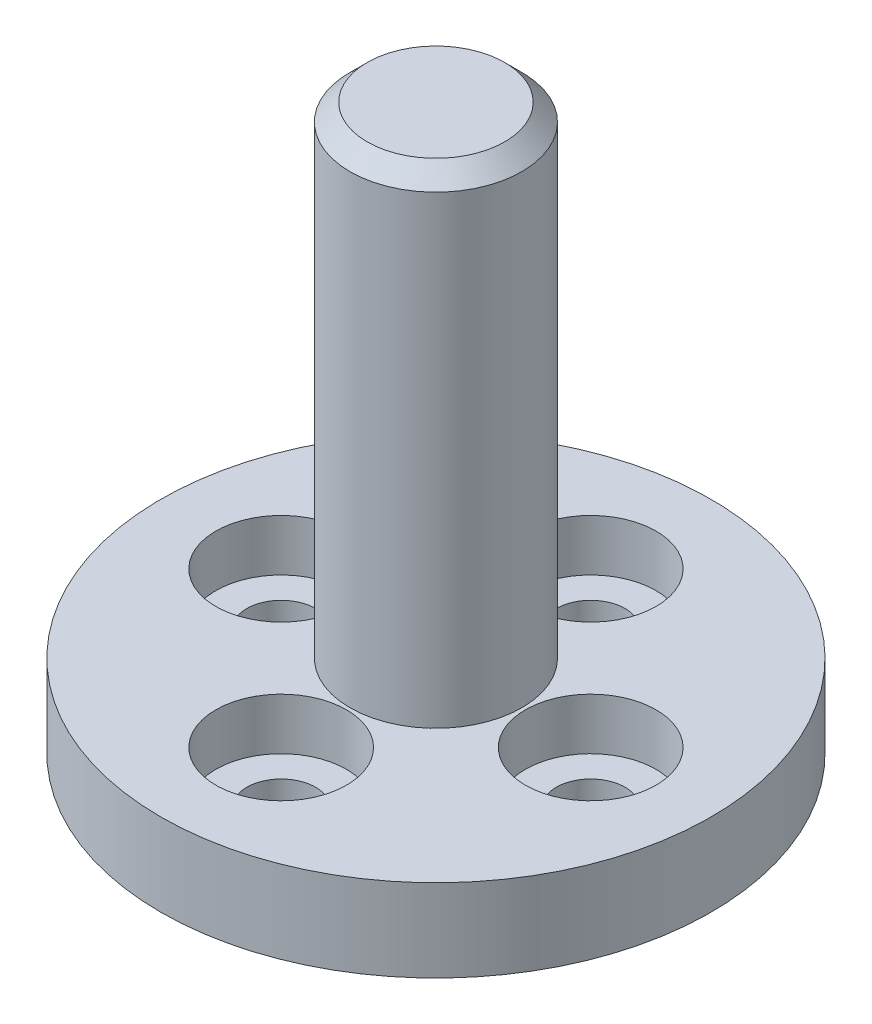
SolidWorks part; units mm, degrees
ref_plane "Plan de face" through (0, 0, 0) normal (0, 0, 1) x (1, 0, 0)
ref_plane "Plan de dessus" through (0, 0, 0) normal (0, 1, 0) x (1, 0, 0)
ref_plane "Plan de droite" through (0, 0, 0) normal (1, 0, 0) x (0, 0, -1)
sketch "Esquisse1" plane through (0, 0, 0) normal (0, 1, 0) x (1, 0, 0)
  circle A0 centre (0, 0) radius 8
  dimension "D1" = 16
extrude "Boss.-Extru.1" add sketch "Esquisse1" along normal blind 2.4
sketch "Esquisse2" plane through (0, 2.4, 0) normal (0, 1, 0) x (1, 0, 0)
  circle A0 centre (0, 0) radius 2.5
  dimension "D1" = 5
extrude "Boss.-Extru.2" add sketch "Esquisse2" along normal blind 14
sketch "Esquisse3" plane through (0, 2.4, 0) normal (0, 1, 0) x (1, 0, 0)
  line L0 (0, 0) -> (4.5, 0) construction
  circle A0 centre (4.5, 0) radius 1
  dimension "D2" = 2
  dimension "D1" = 4.5
extrude "Enlèv. mat.-Extru.1" cut sketch "Esquisse3" against normal blind 7
sketch "Esquisse4" plane through (0, 2.4, 0) normal (0, 1, 0) x (1, 0, 0)
  circle A0 centre (4.5, 0) radius 1.9
  dimension "D1" = 3.8
extrude "Enlèv. mat.-Extru.2" cut sketch "Esquisse4" against normal blind 1.5
pattern_circular "Répétition circulaire2" count 4 over 360 about axis through (0, 0, 0) along (0, 1, 0) of "Enlèv. mat.-Extru.2", "Enlèv. mat.-Extru.1"
chamfer "Chanfrein1" distance 0.5 angle 45 1 edges at (0, 16.4, 2.5)
sketch "Esquisse5" plane through (0, 0, 0) normal (0, -1, 0) x (1, 0, 0)
  circle A0 centre (0, 0) radius 1
  dimension "D1" = 2
extrude "Enlèv. mat.-Extru.3" cut sketch "Esquisse5" against normal blind 1.6
